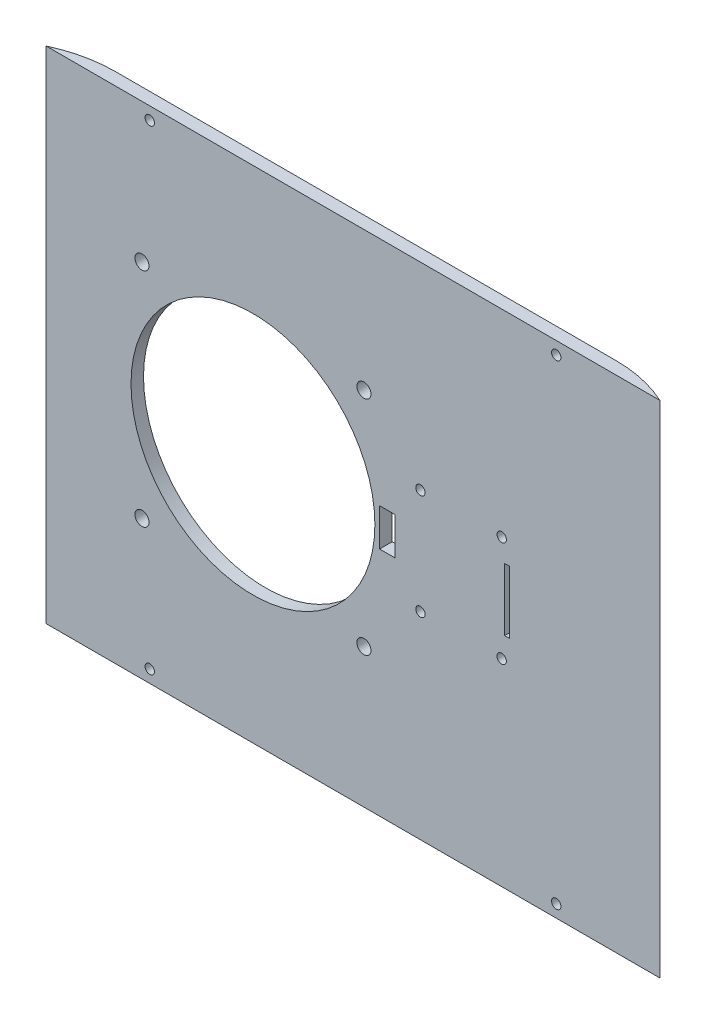
SolidWorks part; units mm, degrees
ref_plane "Piano frontale" through (0, 0, 0) normal (0, 0, 1) x (1, 0, 0)
ref_plane "Piano superiore" through (0, 0, 0) normal (0, 1, 0) x (1, 0, 0)
ref_plane "Piano destro" through (0, 0, 0) normal (1, 0, 0) x (0, 0, -1)
sketch "Schizzo1" plane through (0, 0, 0) normal (0, 0, 1) x (1, 0, 0)
  line L0 (-68.4839, 93.01) -> (-68.4839, -66.99) construction
  line L1 (-83.4839, 93.01) -> (76.5161, 93.01)
  line L2 (-83.4839, 93.01) -> (-83.4839, -66.99)
  line L3 (-83.4839, -66.99) -> (76.5161, -66.99)
  line L4 (76.5161, 93.01) -> (76.5161, -66.99)
  line L5 (61.5161, 93.01) -> (61.5161, -66.99) construction
  circle A0 centre (-68.4839, 89.01) radius 1.5
  circle A1 centre (61.5161, 89.01) radius 1.5
  circle A2 centre (-68.4839, -62.99) radius 1.5
  circle A3 centre (61.5161, -62.99) radius 1.5
  dimension "D5" = 3
  dimension "D6" = 3
  dimension "D7" = 3
  dimension "D11" = 3
  dimension "D1" = 160
  dimension "D2" = 160
  dimension "D3" = 15
  dimension "D4" = 15
  dimension "D8" = 4
  dimension "D9" = 4
  dimension "D10" = 4
  dimension "D12" = 4
extrude "Estrusione-Estrusione1" add sketch "Schizzo1" along normal blind 4
sketch "Schizzo2" plane through (0, 0, 0) normal (0, 0, -1) x (-1, 0, 0)
  line L0 (-76.5161, 93.01) -> (-46.5161, 93.01) construction
  line L1 (-76.5161, 93.01) -> (83.4839, 93.01) construction
  line L2 (-46.5161, 93.01) -> (-46.5161, -66.99) construction
  line L3 (83.4839, -66.99) -> (-76.5161, -66.99) construction
  line L4 (-46.5161, 13.01) -> (-15.359, 13.01) construction
  line L5 (-46.5161, 33.01) -> (-15.6387, 33.01) construction
  line L10 (-15.6387, 33.01) -> (-15.6387, -6.99) construction
  line L11 (-15.6387, -6.99) -> (-46.5161, -6.99) construction
  line L12 (-46.5161, 33.01) -> (-15.6387, -6.99) construction
  line L13 (-15.6387, 33.01) -> (-46.5161, -6.99) construction
  line L14 (-46.5161, 23.01) -> (-45.0161, 23.01)
  line L15 (-45.0161, 23.01) -> (-45.0161, 3.01)
  line L16 (-45.0161, 3.01) -> (-46.5161, 3.01)
  line L17 (-46.5161, 3.01) -> (-46.5161, 23.01)
  circle A0 centre (-44.0719, 29.8436) radius 1.5
  circle A1 centre (-44.0719, -3.8236) radius 1.5
  circle A2 centre (-18.0829, -3.8236) radius 1.5
  circle A3 centre (-18.0829, 29.8436) radius 1.5
  dimension "D5" = 3
  dimension "D6" = 3
  dimension "D7" = 3
  dimension "D8" = 3
  dimension "D1" = 30
  dimension "D2" = 20
  dimension "D3" = 30.8774
  dimension "D4" = 40
  dimension "D9" = 4
  dimension "D10" = 4
  dimension "D11" = 4
  dimension "D12" = 4
  dimension "D13" = 1.5
  dimension "D14" = 10
  dimension "D15" = 20
extrude "Taglio-Estrusione1" cut sketch "Schizzo2" against normal blind 36
sketch "Schizzo3" plane through (0, 0, 0) normal (0, 0, -1) x (-1, 0, 0)
  line L0 (83.4839, 13.01) -> (35.4839, 13.01) construction
  line L1 (83.4839, 93.01) -> (83.4839, -66.99) construction
  line L2 (35.4839, 13.01) -> (35.4839, 52.01) construction
  line L3 (35.4839, 13.01) -> (70.9839, 48.51) construction
  line L4 (35.4839, 13.01) -> (-7.5161, 13.01) construction
  line L6 (-5.0161, 7.01) -> (-10.0161, 7.01)
  line L7 (-5.0161, 7.01) -> (-5.0161, 19.01)
  line L8 (-5.0161, 19.01) -> (-10.0161, 19.01)
  line L9 (-10.0161, 7.01) -> (-10.0161, 19.01)
  line L10 (-5.0161, 7.01) -> (-10.0161, 19.01) construction
  line L11 (-5.0161, 19.01) -> (-10.0161, 7.01) construction
  circle A0 centre (35.4839, 13.01) radius 39
  circle A1 centre (70.9839, 48.51) radius 2.25
  circle A2 centre (70.9839, -22.49) radius 2.25
  circle A3 centre (-0.0161, 48.51) radius 2.25
  circle A4 centre (-0.0161, -22.49) radius 2.25
  dimension "D1" = 78
  dimension "D5" = 4.5
  dimension "D2" = 48
  dimension "D3" = 45
  dimension "D4" = 50.2046
  dimension "D6" = 43
  dimension "D7" = 12
  dimension "D8" = 5
extrude "Taglio-Estrusione2" cut sketch "Schizzo3" against normal blind 7
sketch "Schizzo4" plane through (-83.4839, 0, 0) normal (-1, 0, 0) x (0, 0, 1)
  line L1 (4, -66.99) -> (0, -66.99)
  line L2 (4, -66.99) -> (4, 93.01)
  line L3 (4, 93.01) -> (0, 93.01)
  line L4 (0, -66.99) -> (0, 93.01)
extrude "Estrusione-Estrusione2" add sketch "Schizzo4" along normal blind 18.1384
sketch "Schizzo5" plane through (76.5161, 0, 0) normal (1, 0, 0) x (0, 0, -1)
  line L1 (0, 93.01) -> (-4, 93.01)
  line L2 (0, 93.01) -> (0, -66.99)
  line L3 (0, -66.99) -> (-4, -66.99)
  line L4 (-4, 93.01) -> (-4, -66.99)
extrude "Estrusione-Estrusione3" add sketch "Schizzo5" along normal blind 18.1384
sketch "Schizzo6" plane through (0, 93.01, 0) normal (0, 1, 0) x (1, 0, 0)
  line L0 (-101.6222, 0) -> (-83.4839, 0) construction
  line L1 (94.6545, 0) -> (-101.6222, 0) construction
  line L2 (94.6545, 0) -> (76.5161, 0) construction
  line L3 (-83.4839, 0) -> (76.5161, 0) construction
  line L4 (-101.6222, -4) -> (94.6545, -4) construction
  line L5 (-101.6222, -4) -> (-101.6222, 0)
  line L6 (-101.6222, 0) -> (-83.4839, 0)
  line L7 (76.5161, 0) -> (94.6545, 0)
  line L8 (94.6545, 0) -> (94.6545, -4)
  arc A0 (-83.4839, 0) -> (-101.6222, -4) centre (-83.4839, -43.125) ccw
  arc A1 (76.5161, 0) -> (94.6545, -4) centre (76.5161, -43.125) cw
  dimension "D1" = 18.1384
  dimension "D2" = 18.1384
extrude "Taglio-Estrusione3" cut sketch "Schizzo6" against normal blind 229.1384
